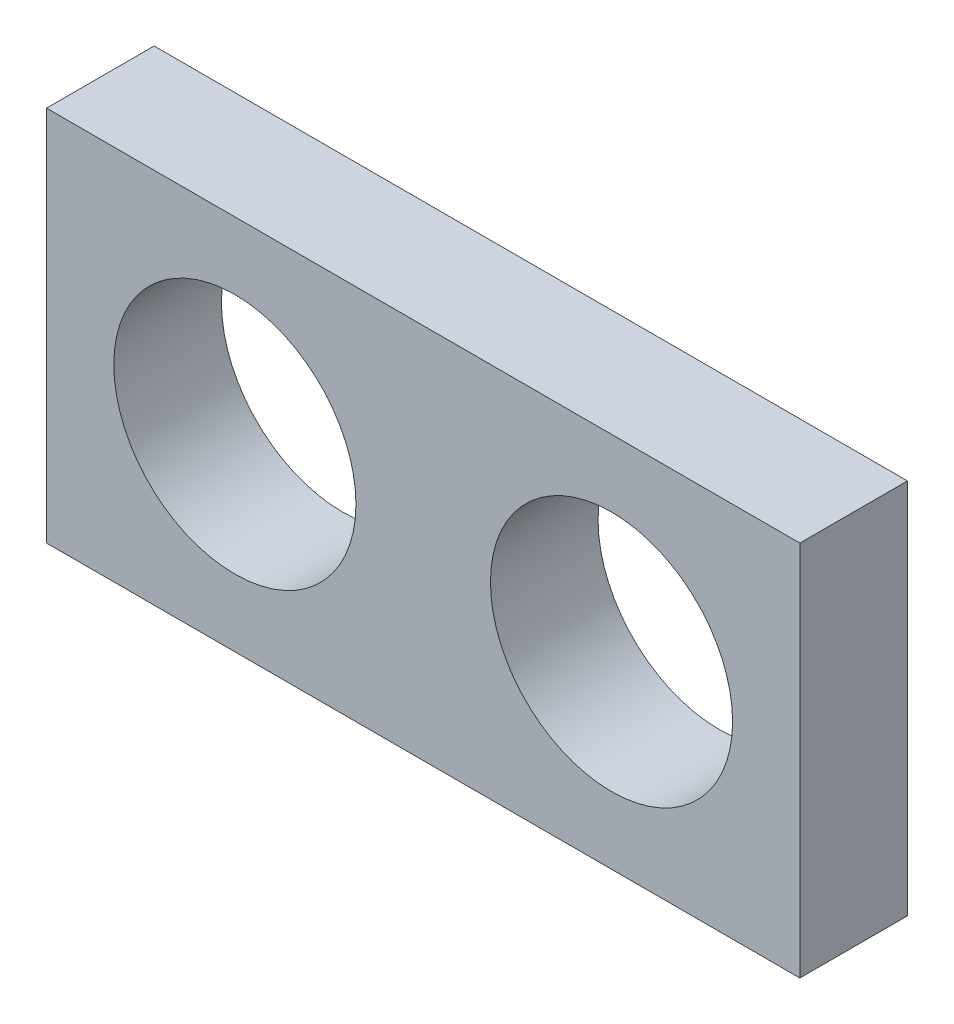
SolidWorks part; units mm, degrees
ref_plane "Plan de face" through (0, 0, 0) normal (0, 0, 1) x (1, 0, 0)
ref_plane "Plan de dessus" through (0, 0, 0) normal (0, 1, 0) x (1, 0, 0)
ref_plane "Plan de droite" through (0, 0, 0) normal (1, 0, 0) x (0, 0, -1)
sketch "Esquisse1" plane through (0, 0, 0) normal (0, 0, 1) x (1, 0, 0)
  line L1 (1.7549, 3.6603) -> (15.7549, 3.6603)
  line L2 (1.7549, 3.6603) -> (1.7549, -3.3397)
  line L3 (1.7549, -3.3397) -> (15.7549, -3.3397)
  line L4 (15.7549, 3.6603) -> (15.7549, -3.3397)
  circle A0 centre (5.2549, 0.1603) radius 2.25
  circle A1 centre (12.2549, 0.1603) radius 2.25
  point P8 (0, 0)
  point P10 (7.3429, 3.0778)
  dimension "D1" = 4.5
  dimension "D2" = 4.5
  dimension "D3" = 7
  dimension "D4" = 7
  dimension "D5" = 3.5
  dimension "D6" = 3.5
  dimension "D7" = 3.5
extrude "Boss.-Extru.1" add sketch "Esquisse1" along normal blind 2
